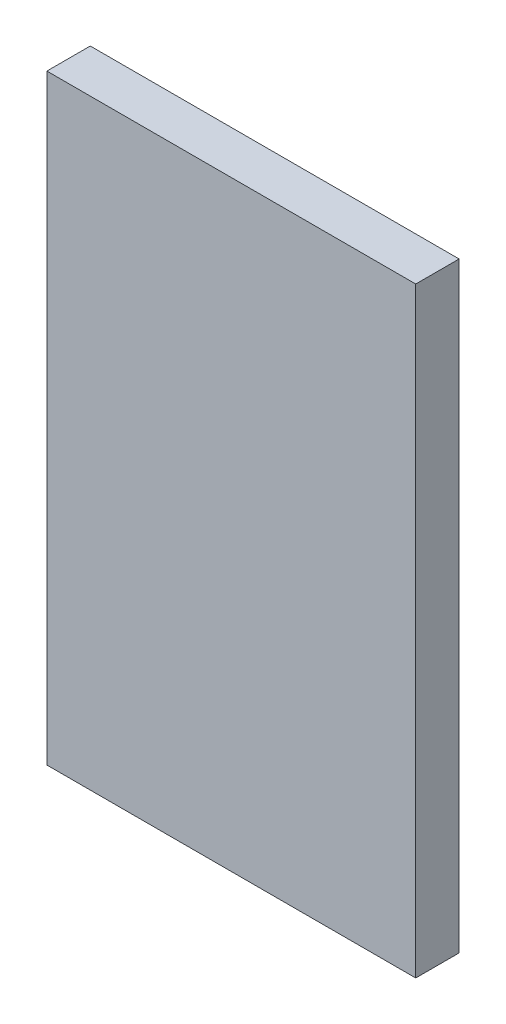
SolidWorks part; units mm, degrees
ref_plane "Alzado" through (0, 0, 0) normal (0, 0, 1) x (1, 0, 0)
ref_plane "Planta" through (0, 0, 0) normal (0, 1, 0) x (1, 0, 0)
ref_plane "Vista lateral" through (0, 0, 0) normal (1, 0, 0) x (0, 0, -1)
sketch "Croquis1" plane through (0, 0, 0) normal (0, 0, 1) x (1, 0, 0)
  line L1 (8.5, -13.85) -> (-8.5, -13.85)
  line L2 (8.5, -13.85) -> (8.5, 13.85)
  line L3 (8.5, 13.85) -> (-8.5, 13.85)
  line L4 (-8.5, -13.85) -> (-8.5, 13.85)
  line L5 (8.5, -13.85) -> (-8.5, 13.85) construction
  line L6 (8.5, 13.85) -> (-8.5, -13.85) construction
  point P0 (0, 0)
  dimension "D1" = 17
  dimension "D2" = 27.7
extrude "Saliente-Extruir1" add sketch "Croquis1" along normal blind 2
